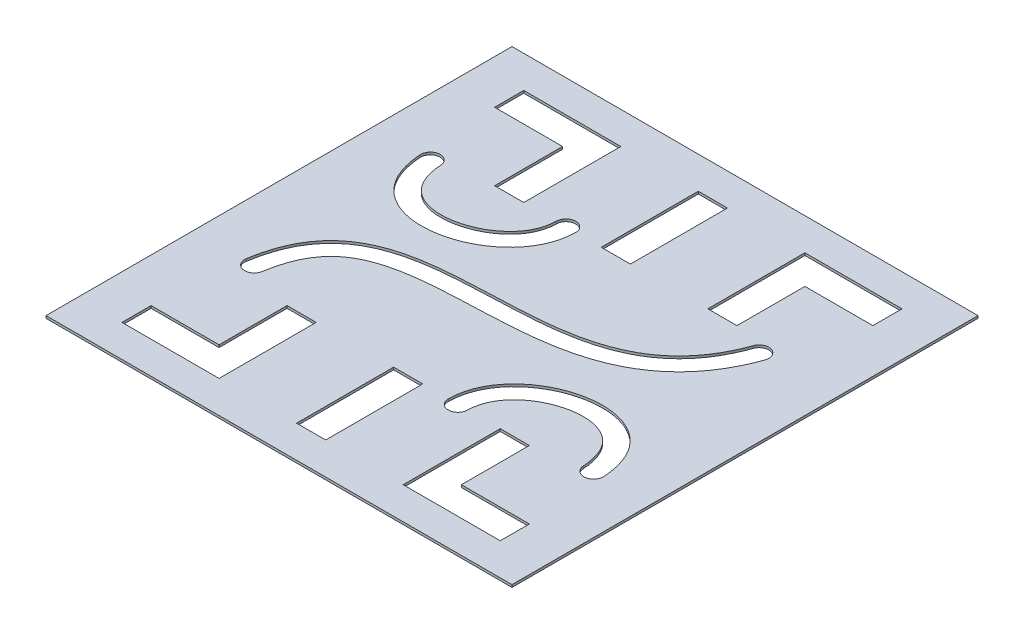
SolidWorks part; units mm, degrees
ref_plane "Front Plane" through (0, 0, 0) normal (0, 0, 1) x (1, 0, 0)
ref_plane "Top Plane" through (0, 0, 0) normal (0, 1, 0) x (1, 0, 0)
ref_plane "Right Plane" through (0, 0, 0) normal (1, 0, 0) x (0, 0, -1)
sketch "Sketch1" plane through (0, 0, 0) normal (0, 1, 0) x (1, 0, 0)
  line L0 (0, 304.8) -> (0, -304.8) construction
  line L1 (-304.8, 304.8) -> (304.8, 304.8)
  line L2 (-304.8, 304.8) -> (-304.8, -304.8)
  line L3 (-304.8, -304.8) -> (304.8, -304.8)
  line L4 (304.8, 304.8) -> (304.8, -304.8)
  line L5 (-304.8, 304.8) -> (304.8, -304.8) construction
  line L6 (-304.8, -304.8) -> (304.8, 304.8) construction
  line L7 (-304.8, 0) -> (304.8, 0) construction
  line L8 (120.4082, 135.7792) -> (120.4082, 262.7792)
  line L9 (-19.05, 262.7792) -> (19.05, 262.7792)
  line L10 (-19.05, 262.7792) -> (-19.05, 135.7792)
  line L11 (-19.05, 135.7792) -> (19.05, 135.7792)
  line L12 (19.05, 262.7792) -> (19.05, 135.7792)
  line L13 (-19.05, 262.7792) -> (19.05, 135.7792) construction
  line L14 (-19.05, 135.7792) -> (19.05, 262.7792) construction
  line L19 (120.4082, 262.7792) -> (247.4082, 262.7792)
  line L20 (247.4082, 262.7792) -> (247.4082, 224.6792)
  line L21 (247.4082, 224.6792) -> (158.5082, 224.6792)
  line L22 (158.5082, 224.6792) -> (158.5082, 135.7792)
  line L23 (158.5082, 135.7792) -> (120.4082, 135.7792)
  line L24 (0, -335.28) -> (0, 335.28) construction
  line L25 (-158.5082, 224.6792) -> (-158.5082, 135.7792)
  line L26 (-247.4082, 224.6792) -> (-158.5082, 224.6792)
  line L27 (-247.4082, 262.7792) -> (-247.4082, 224.6792)
  line L28 (-120.4082, 262.7792) -> (-247.4082, 262.7792)
  line L29 (-120.4082, 135.7792) -> (-120.4082, 262.7792)
  line L30 (-158.5082, 135.7792) -> (-120.4082, 135.7792)
  line L31 (-335.28, 0) -> (335.28, 0) construction
  line L32 (158.5082, -224.6792) -> (158.5082, -135.7792)
  line L33 (247.4082, -224.6792) -> (158.5082, -224.6792)
  line L34 (247.4082, -262.7792) -> (247.4082, -224.6792)
  line L35 (120.4082, -262.7792) -> (247.4082, -262.7792)
  line L36 (120.4082, -135.7792) -> (120.4082, -262.7792)
  line L37 (158.5082, -135.7792) -> (120.4082, -135.7792)
  line L38 (-19.05, -135.7792) -> (19.05, -135.7792)
  line L39 (19.05, -262.7792) -> (19.05, -135.7792)
  line L40 (-19.05, -262.7792) -> (19.05, -262.7792)
  line L41 (-19.05, -262.7792) -> (-19.05, -135.7792)
  line L42 (-247.4082, -224.6792) -> (-158.5082, -224.6792)
  line L43 (-247.4082, -262.7792) -> (-247.4082, -224.6792)
  line L44 (-120.4082, -262.7792) -> (-247.4082, -262.7792)
  line L45 (-120.4082, -135.7792) -> (-120.4082, -262.7792)
  line L46 (-158.5082, -135.7792) -> (-120.4082, -135.7792)
  line L47 (-158.5082, -224.6792) -> (-158.5082, -135.7792)
  line L48 (52.5513, -135.7792) -> (77.9494, -136.0952) construction
  line L49 (216.9711, -123.7397) -> (242.3205, -122.1367) construction
  line L50 (-238.3618, -109.2761) -> (-213.2715, -113.2304) construction
  line L51 (215.7639, 115.203) -> (191.8415, 123.7397) construction
  arc A0 (52.5513, -135.7792) -> (77.9494, -136.0952) centre (65.2503, -135.9372) ccw
  arc A1 (216.9711, -123.7397) -> (242.3205, -122.1367) centre (229.6458, -122.9382) ccw
  arc A2 (-52.5513, 135.7792) -> (-77.9494, 136.0952) centre (-65.2503, 135.9372) ccw
  arc A3 (-216.9711, 123.7397) -> (-242.3205, 122.1367) centre (-229.6458, 122.9382) ccw
  arc A4 (-238.3618, -109.2761) -> (-213.2715, -113.2304) centre (-225.8167, -111.2533) ccw
  arc A5 (191.8415, 123.7397) -> (215.7639, 115.203) centre (203.8027, 119.4713) cw
  spline S0 degree 3 poles (52.5513, -135.7792) (53.804, -35.1041) (234.2787, 5.0362) (242.3205, -122.1367) knots 0 0 0 0 1 1 1 1
  spline S1 degree 1 poles (77.9494, -136.0952) (216.9711, -123.7397) knots 0 0 1 1 construction
  spline S2 degree 3 poles (77.9494, -136.0952) (77.9629, -135.0098) (78.0515, -132.82) (78.461, -128.6107) (79.3918, -123.5299) (81.1406, -117.7021) (84.2883, -110.2283) (89.7249, -101.3987) (98.52, -91.7309) (109.2965, -83.2916) (125.71, -74.0977) (144.1075, -68.5898) (162.0083, -67.3968) (174.5626, -68.638) (185.7302, -71.9022) (195.2308, -77.0141) (201.8209, -82.8199) (206.399, -88.6542) (209.4813, -93.7434) (212.1774, -99.6678) (214.0425, -105.4004) (215.2558, -110.5141) (216.0119, -114.621) (216.502, -118.2834) (216.8017, -121.3461) (216.921, -122.947) (216.9711, -123.7397) knots 0 0 0 0 0.015625 0.03125 0.0625 0.09375 0.125 0.1875 0.25 0.3125 0.375 0.5 0.5625 0.625 0.6875 0.75 0.8125 0.84375 0.875 0.90625 0.9375 0.953125 0.96875 0.984375 0.992188 1 1 1 1
  spline S3 degree 3 poles (-52.5513, 135.7792) (-53.804, 35.1041) (-234.2787, -5.0362) (-242.3205, 122.1367) knots 0 0 0 0 1 1 1 1
  spline S4 degree 3 poles (-77.9494, 136.0952) (-77.9629, 135.0098) (-78.0515, 132.82) (-78.461, 128.6107) (-79.3918, 123.5299) (-81.1406, 117.7021) (-84.2883, 110.2283) (-89.7249, 101.3987) (-98.52, 91.7309) (-109.2965, 83.2916) (-125.71, 74.0977) (-144.1075, 68.5898) (-162.0083, 67.3968) (-174.5626, 68.638) (-185.7302, 71.9022) (-195.2308, 77.0141) (-201.8209, 82.8199) (-206.399, 88.6542) (-209.4813, 93.7434) (-212.1774, 99.6678) (-214.0425, 105.4004) (-215.2558, 110.5141) (-216.0119, 114.621) (-216.502, 118.2834) (-216.8017, 121.3461) (-216.921, 122.947) (-216.9711, 123.7397) knots 0 0 0 0 0.015625 0.03125 0.0625 0.09375 0.125 0.1875 0.25 0.3125 0.375 0.5 0.5625 0.625 0.6875 0.75 0.8125 0.84375 0.875 0.90625 0.9375 0.953125 0.96875 0.984375 0.992188 1 1 1 1
  spline S5 degree 3 poles (-238.3618, -109.2761) (-231.8372, -67.8776) (-143.9476, 74.8456) (129.5993, -50.6813) (191.8415, 123.7397) knots 0 0 0 0 0.18644 1 1 1 1
  spline S6 degree 1 poles (-213.2715, -113.2304) (215.7639, 115.203) knots 0 0 1 1 construction
  spline S7 degree 3 poles (-213.2715, -113.2304) (-213.1517, -112.4703) (-212.9014, -110.9421) (-212.3765, -107.9679) (-211.6674, -104.3503) (-210.7377, -100.1831) (-209.3963, -94.8487) (-207.5373, -88.5904) (-205.0396, -81.7035) (-202.2977, -75.4032) (-198.3403, -67.7288) (-192.8647, -59.3833) (-185.4694, -50.9787) (-177.1596, -43.8399) (-167.7991, -37.7316) (-153.7842, -30.7921) (-133.2851, -24.2285) (-104.4531, -19.3302) (-72.3859, -16.6822) (-38.0558, -15.2671) (-2.333, -13.9139) (34.0247, -11.3469) (70.348, -6.174) (105.9832, 3.167) (134.3999, 15.9162) (155.6427, 29.9561) (170.5806, 42.5563) (184.2788, 57.3204) (194.4781, 71.4533) (201.8305, 83.8617) (206.9278, 93.718) (210.8224, 102.4013) (213.7159, 109.6137) (215.0996, 113.3414) (215.7639, 115.203) knots 0 0 0 0 0.003906 0.007812 0.015625 0.023438 0.03125 0.046875 0.0625 0.078125 0.09375 0.125 0.15625 0.1875 0.21875 0.25 0.3125 0.375 0.4375 0.5 0.5625 0.625 0.6875 0.75 0.8125 0.84375 0.875 0.90625 0.9375 0.953125 0.96875 0.984375 0.992188 1 1 1 1
  point P0 (0, 0)
  point P10 (0, 199.2792)
  point P70 (0, 0)
  dimension "D1" = 609.6
  dimension "D2" = 609.6
  dimension "D3" = 38.1
  dimension "D4" = 38.1
  dimension "D5" = 38.1
  dimension "D6" = 127
  dimension "D7" = 127
  dimension "D8" = 127
  dimension "D9" = 25.4
  dimension "D11" = 25.4
  dimension "D10" = 2
extrude "Boss-Extrude1" add sketch "Sketch1" along normal blind 3.175 contours L4 L1 L2 L3 S7 A4 S5 A5 S4 A2 S3 A3 S2 A0 S0 A1 L37 L32 L33 L34 L35 L36 L30 L25 L26 L27 L28 L29 L9 L12 L11 L10 L22 L23 L8 L19 L20 L21 L40 L41 L38 L39
